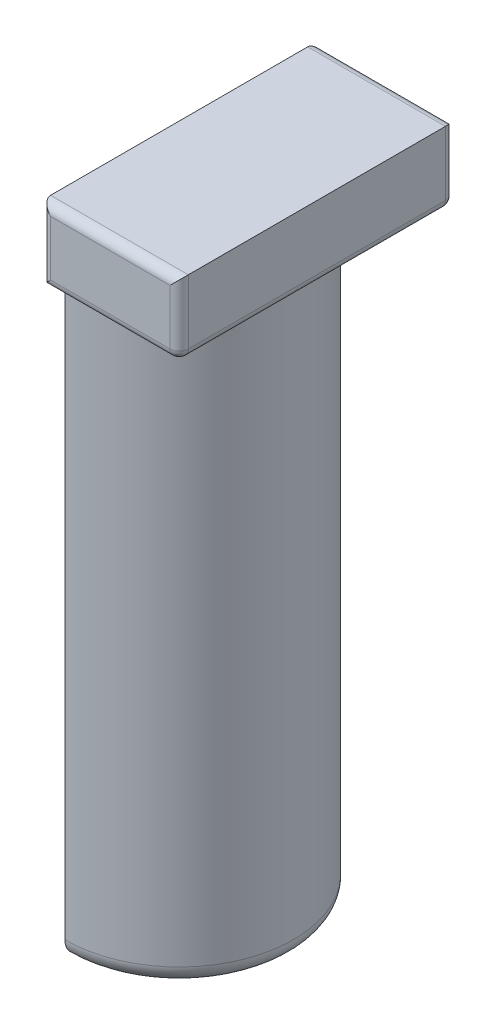
SolidWorks part; units mm, degrees
ref_plane "前视基准面" through (0, 0, 0) normal (0, 0, 1) x (1, 0, 0)
ref_plane "上视基准面" through (0, 0, 0) normal (0, 1, 0) x (1, 0, 0)
ref_plane "右视基准面" through (0, 0, 0) normal (1, 0, 0) x (0, 0, -1)
other "Configuration Table"
sketch "草图1" plane through (0, 0, 0) normal (0, 1, 0) x (1, 0, 0)
  line L1 (0, 0) -> (-30, 0)
  line L2 (0, 0) -> (0, 30)
  line L3 (0, 30) -> (-30, 30)
  line L4 (-30, 0) -> (-30, 30)
  dimension "D1" = 30
  dimension "D2" = 30
extrude "凸台-拉伸1" add sketch "草图1" along normal blind 8
sketch "草图2" plane through (0, 0, 0) normal (0, -1, 0) x (1, 0, 0)
  line L0 (-30, 0) -> (0, 0) construction
  line L1 (-30, -30) -> (-30, 0) construction
  circle A0 centre (-15, -15) radius 12.45
  dimension "D2" = 15
  dimension "D3" = 24.9
  dimension "D1" = 15
extrude "凸台-拉伸2" add sketch "草图2" along normal blind 65
sketch "草图3" plane through (0, 8, 0) normal (0, 1, 0) x (1, 0, 0)
  line L0 (0, 30) -> (-30, 30) construction
  line L1 (-15, 30) -> (-30, 30)
  line L2 (-15, 30) -> (-15, 0)
  line L3 (-15, 0) -> (-30, 0)
  line L4 (-30, 30) -> (-30, 0)
extrude "切除-拉伸1" cut sketch "草图3" against normal through all
fillet "圆角1" radius 2 1 edges at (-2.55, -65, -15)
fillet "圆角2" radius 1 9 edges at (0, 4, -30) (-7.5, 8, -30) (-15, 4, -30) (-7.5, 0, -30) (0, 4, 0) (-7.5, 0, 0) (-15, 4, 0) (-7.5, 8, 0) (0, 0, -15)
